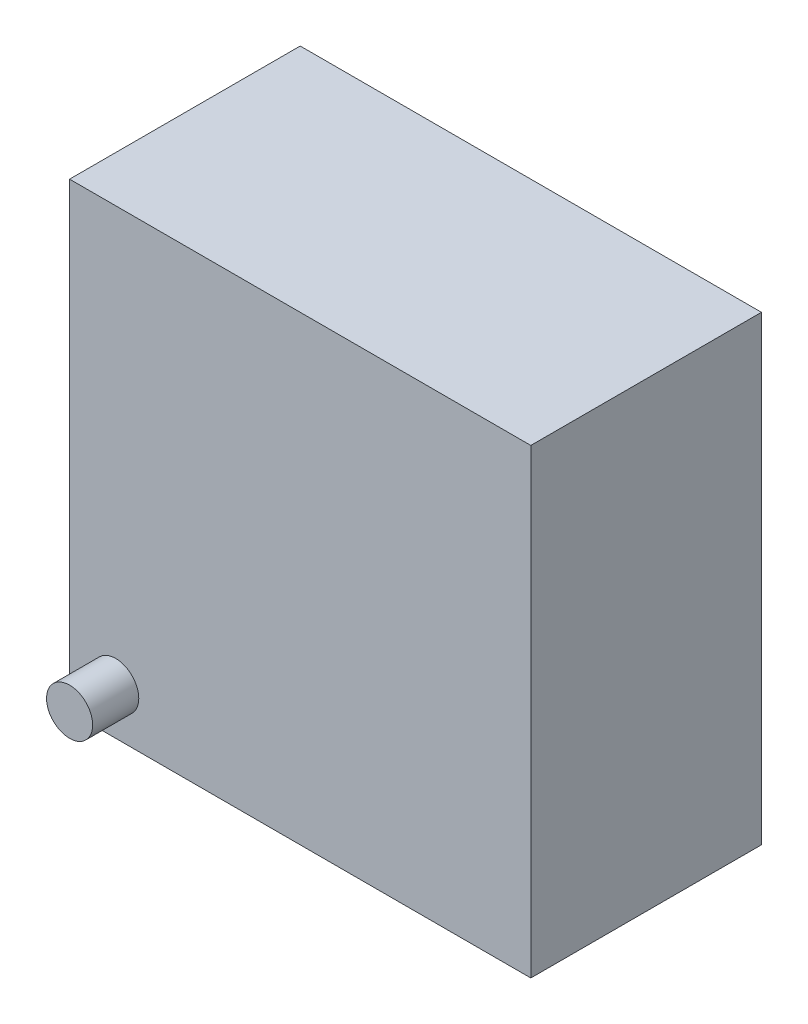
SolidWorks part; units mm, degrees
ref_plane "前视基准面" through (0, 0, 0) normal (0, 0, 1) x (1, 0, 0)
ref_plane "上视基准面" through (0, 0, 0) normal (0, 1, 0) x (1, 0, 0)
ref_plane "右视基准面" through (0, 0, 0) normal (1, 0, 0) x (0, 0, -1)
other "Configuration Table"
sketch "草图1" plane through (0, 0, 0) normal (0, 0, 1) x (1, 0, 0)
  line L1 (0, 0) -> (20, 0)
  line L2 (0, 0) -> (0, 20)
  line L3 (0, 20) -> (20, 20)
  line L4 (20, 0) -> (20, 20)
extrude "BaseBox" add sketch "草图1" along normal blind 10
sketch "草图2" plane through (0, 0, 10) normal (0, 0, 1) x (1, 0, 0)
  circle A0 centre (2, 2) radius 1
extrude "BossSeed" add sketch "草图2" along normal blind 2
pattern_linear "LinearPattern" count 3 spacing 15 along (-1, 0, 0) of "BossSeed"
